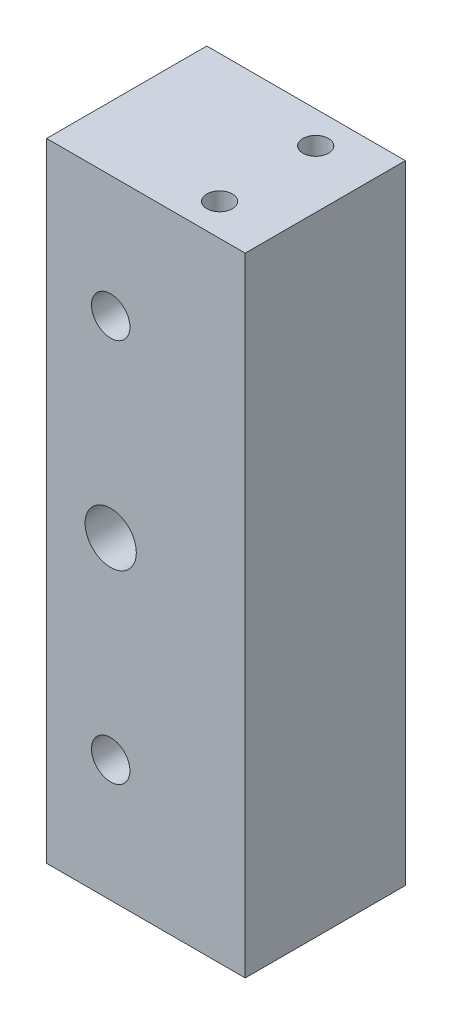
SolidWorks part; units mm, degrees
ref_plane "Front Plane" through (0, 0, 0) normal (0, 0, 1) x (1, 0, 0)
ref_plane "Top Plane" through (0, 0, 0) normal (0, 1, 0) x (1, 0, 0)
ref_plane "Right Plane" through (0, 0, 0) normal (1, 0, 0) x (0, 0, -1)
sketch "Sketch1" plane through (0, 0, 0) normal (0, 0, 1) x (1, 0, 0)
  line L0 (0, 54.72) -> (0, -59.6571) construction
  line L1 (-10, -49) -> (10, -49)
  line L2 (-10, -49) -> (-10, 49)
  line L3 (-10, 49) -> (10, 49)
  line L4 (10, -49) -> (10, 49)
  line L5 (-10, -49) -> (10, 49) construction
  line L6 (-10, 49) -> (10, -49) construction
  circle A0 centre (0, 0) radius 4
  circle A1 centre (0, -30) radius 3
  circle A2 centre (0, 30) radius 3
  dimension "D1" = 8
  dimension "D4" = 6
  dimension "D5" = 6
  dimension "D2" = 98
  dimension "D3" = 20
  dimension "D6" = 30
  dimension "D7" = 60
extrude "Boss-Extrude1" add sketch "Sketch1" along normal blind 25
sketch "Sketch2" plane through (0, 0, 0) normal (0, 0, -1) x (-1, 0, 0)
  line L0 (-12, 48.9915) -> (-12, -48.9915) construction
  line L1 (-10, 49) -> (-21, 49)
  line L2 (-10, 49) -> (-10, -49)
  line L3 (-10, -49) -> (-21, -49)
  line L4 (-21, -49) -> (-21, 49)
  dimension "D1" = 12
  dimension "D2" = 9
extrude "Boss-Extrude2" add sketch "Sketch2" against normal through all
sketch "Sketch3" plane through (0, 49, 0) normal (0, 1, 0) x (1, 0, 0)
  line L0 (12, -5) -> (12, -20) construction
  line L1 (21, 0) -> (-10, 0) construction
  circle A0 centre (12, -5) radius 2
  circle A1 centre (12, -20) radius 2
  dimension "D1" = 4
  dimension "D2" = 4
  dimension "D3" = 15
  dimension "D4" = 5
  dimension "D5" = 12
extrude "Cut-Extrude1" cut sketch "Sketch3" against normal blind 25
mirror "Mirror1" about plane through (0, 0, 0) normal (0, 1, 0) of "Cut-Extrude1"
equation "\"D5@Sketch1\"=\"D4@Sketch1\""
